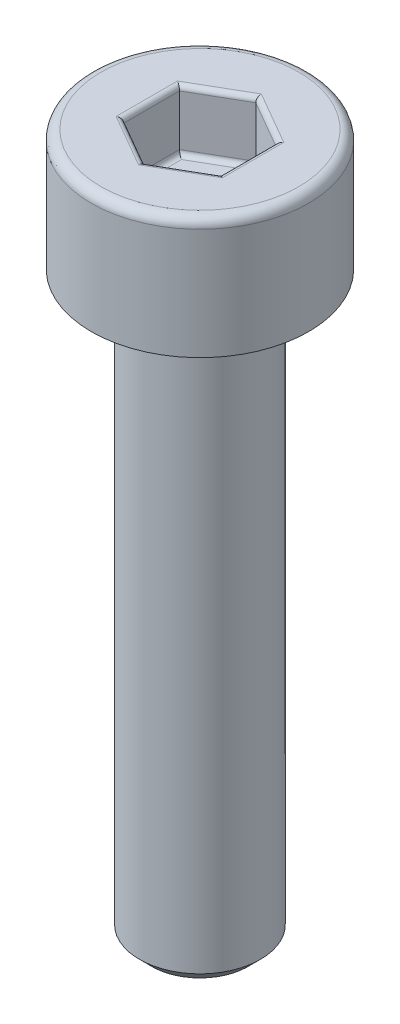
SolidWorks part; units mm, degrees
ref_plane "Front Plane" through (0, 0, 0) normal (0, 0, 1) x (1, 0, 0)
ref_plane "Top Plane" through (0, 0, 0) normal (0, 1, 0) x (1, 0, 0)
ref_plane "Right Plane" through (0, 0, 0) normal (1, 0, 0) x (0, 0, -1)
sketch "Sketch1" plane through (0, 0, 0) normal (0, 0, 1) x (1, 0, 0)
  line L0 (0, 0) -> (0, -47.0967) construction
  line L1 (0, -14.5) -> (-1.25, -14.5)
  line L2 (-1.25, -14.5) -> (-1.25, -2.5)
  line L3 (-1.25, -2.5) -> (-2.25, -2.5)
  line L4 (-2.25, -2.5) -> (-2.25, 0)
  line L5 (-2.25, 0) -> (0, 0)
  line L6 (0, 0) -> (0, -14.5)
  dimension "D1" = 12
  dimension "d" = 2.5
  dimension "k" = 2.5
  dimension "dk" = 4.5
revolve "Revolve1" add sketch "Sketch1" angle 360 about L0
chamfer "Chamfer1" distance 0.25 angle 45 2 edges at (0, -2.5, 1.25) (0, -14.5, 1.25)
fillet "Fillet1" radius 0.2 1 edges at (0, 0, 2.25)
sketch "Sketch2" plane through (0, 0, 0) normal (0, 1, 0) x (1, 0, 0)
  line L1 (0, 1.1547) -> (-1, 0.5774)
  line L2 (-1, 0.5774) -> (-1, -0.5774)
  line L3 (-1, -0.5774) -> (0, -1.1547)
  line L4 (0, -1.1547) -> (1, -0.5774)
  line L5 (1, -0.5774) -> (1, 0.5774)
  line L6 (1, 0.5774) -> (0, 1.1547)
  circle A0 centre (0, 0) radius 1 construction
  dimension "s" = 2
extrude "Cut-Extrude1" cut sketch "Sketch2" against normal blind 1.25
fillet "Fillet2" radius 0.1 12 edges at (-0.5, 0, -0.866) (-1, 0, 0) (-0.5, 0, 0.866) (0.5, 0, 0.866) (1, 0, 0) (0.5, 0, -0.866) (1, -1.25, 0) (0.5, -1.25, 0.866) (-0.5, -1.25, 0.866) (-1, -1.25, 0) (-0.5, -1.25, -0.866) (0.5, -1.25, -0.866)
